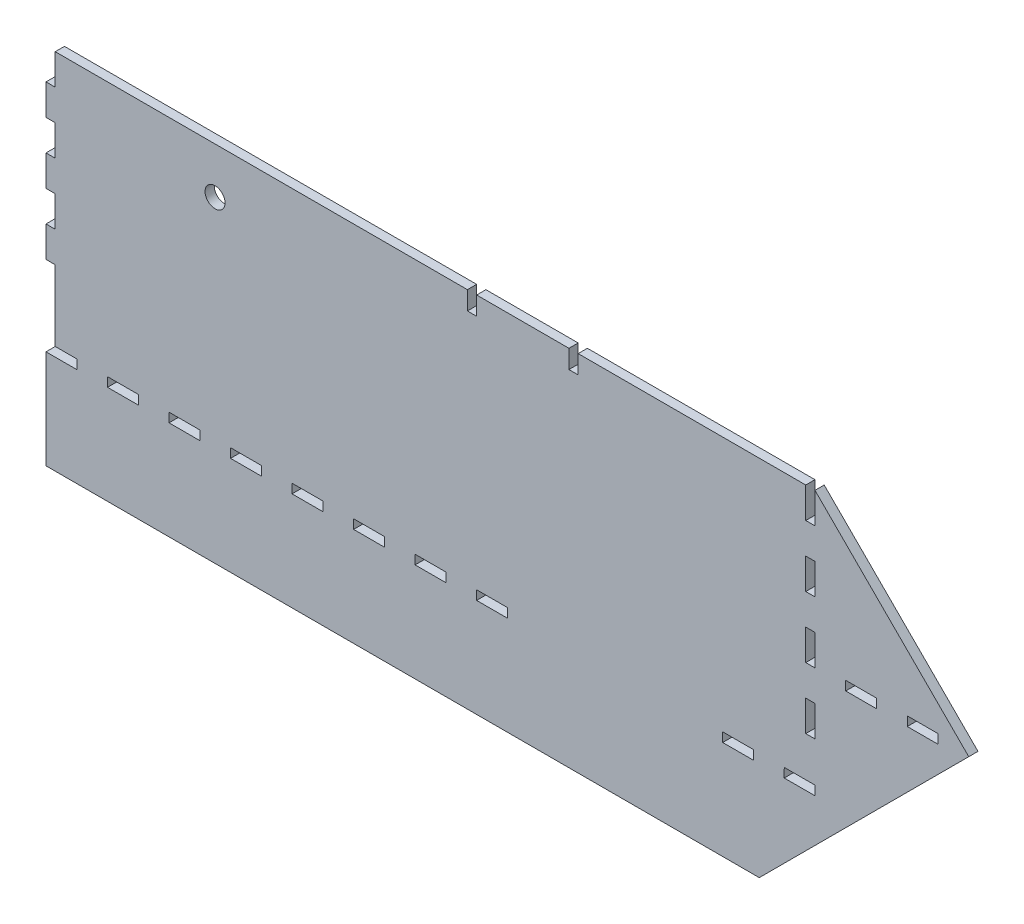
SolidWorks part; units mm, degrees
ref_plane "Front Plane" through (0, 0, 0) normal (0, 0, 1) x (1, 0, 0)
ref_plane "Top Plane" through (0, 0, 0) normal (0, 1, 0) x (1, 0, 0)
ref_plane "Right Plane" through (0, 0, 0) normal (1, 0, 0) x (0, 0, -1)
sketch "Sketch1" plane through (0, 0, 0) normal (0, 0, 1) x (1, 0, 0)
  line L0 (-112.631, -63.8403) -> (-112.631, -53.7284)
  line L1 (134.369, 32.2716) -> (60.379, 32.2716)
  line L2 (-72.631, -50.7284) -> (-62.631, -50.7284)
  line L3 (-62.631, 32.2716) -> (24.379, 32.2716)
  line L4 (137.369, 32.2716) -> (187.369, -17.7284)
  line L5 (187.369, -17.7284) -> (137.369, -67.7284)
  line L6 (-112.631, 17.2716) -> (-57.6695, 17.2716) construction
  line L7 (42.379, 32.2716) -> (27.379, 32.2716)
  line L8 (27.379, 32.2716) -> (27.379, 26.2716)
  line L9 (137.369, 32.2716) -> (137.369, -67.7284) construction
  line L10 (137.369, -17.7284) -> (187.369, -17.7284) construction
  line L11 (157.369, -16.2284) -> (147.369, -16.2284)
  line L12 (177.369, -16.2284) -> (167.369, -16.2284)
  line L13 (177.369, -16.2284) -> (177.369, -19.2284)
  line L14 (177.369, -19.2284) -> (167.369, -19.2284)
  line L15 (167.369, -16.2284) -> (167.369, -19.2284)
  line L16 (177.369, -16.2284) -> (167.369, -19.2284) construction
  line L17 (177.369, -19.2284) -> (167.369, -16.2284) construction
  line L18 (157.369, -16.2284) -> (157.369, -19.2284)
  line L19 (157.369, -19.2284) -> (147.369, -19.2284)
  line L20 (147.369, -16.2284) -> (147.369, -19.2284)
  line L21 (137.3812, -50.7284) -> (127.3812, -50.7284)
  line L22 (137.3812, -50.7284) -> (137.3692, -53.7284)
  line L23 (137.3692, -53.7284) -> (127.3692, -53.7284)
  line L24 (127.3812, -50.7284) -> (127.3692, -53.7284)
  line L25 (137.3812, -50.7284) -> (127.3692, -53.7284) construction
  line L26 (137.3692, -53.7284) -> (127.3812, -50.7284) construction
  line L27 (117.3811, -50.7284) -> (107.3787, -50.7284)
  line L28 (117.3811, -50.7284) -> (117.3691, -53.7284)
  line L29 (117.3691, -53.7284) -> (107.3691, -53.7284)
  line L30 (107.3787, -50.7284) -> (107.3691, -53.7284)
  line L31 (117.3811, -50.7284) -> (107.3691, -53.7284) construction
  line L32 (117.3691, -53.7284) -> (107.3787, -50.7284) construction
  line L33 (27.379, 26.2716) -> (24.379, 26.2716)
  line L34 (24.379, 26.2716) -> (24.379, 32.2716)
  line L35 (27.379, 32.2716) -> (57.379, 32.2716)
  line L36 (137.369, -67.7284) -> (119.2571, -85.8403)
  line L37 (60.379, 26.2716) -> (60.379, 32.2716)
  line L38 (57.379, 26.2716) -> (60.379, 26.2716)
  line L39 (57.379, 32.2716) -> (57.379, 26.2716)
  line L40 (57.379, 32.2716) -> (42.379, 32.2716)
  line L41 (60.379, 32.2716) -> (134.369, 32.2716)
  line L42 (119.2571, -85.8403) -> (-112.631, -85.8403)
  line L43 (-112.631, -85.8403) -> (-112.631, -63.8403)
  line L51 (37.3714, -50.7284) -> (27.369, -50.7284)
  line L52 (37.3714, -50.7284) -> (37.369, -53.7284)
  line L53 (37.369, -53.7284) -> (27.369, -53.7284)
  line L54 (27.369, -50.7284) -> (27.369, -53.7284)
  line L55 (37.3714, -50.7284) -> (27.369, -53.7284) construction
  line L56 (37.369, -53.7284) -> (27.369, -50.7284) construction
  line L57 (17.369, -50.7284) -> (7.369, -50.7284)
  line L58 (17.369, -50.7284) -> (17.369, -53.7284)
  line L59 (17.369, -53.7284) -> (7.369, -53.7284)
  line L60 (7.369, -50.7284) -> (7.369, -53.7284)
  line L61 (17.369, -50.7284) -> (7.369, -53.7284) construction
  line L62 (17.369, -53.7284) -> (7.369, -50.7284) construction
  line L63 (-2.631, -50.7284) -> (-12.631, -50.7284)
  line L64 (-2.631, -50.7284) -> (-2.631, -53.7284)
  line L65 (-2.631, -53.7284) -> (-12.631, -53.7284)
  line L66 (-12.631, -50.7284) -> (-12.631, -53.7284)
  line L67 (-2.631, -50.7284) -> (-12.631, -53.7284) construction
  line L68 (-2.631, -53.7284) -> (-12.631, -50.7284) construction
  line L69 (-22.631, -50.7284) -> (-32.631, -50.7284)
  line L70 (-22.631, -50.7284) -> (-22.631, -53.7284)
  line L71 (-22.631, -53.7284) -> (-32.631, -53.7284)
  line L72 (-32.631, -50.7284) -> (-32.631, -53.7284)
  line L73 (-22.631, -50.7284) -> (-32.631, -53.7284) construction
  line L74 (-22.631, -53.7284) -> (-32.631, -50.7284) construction
  line L75 (-42.631, -50.7284) -> (-52.631, -50.7284)
  line L76 (-42.631, -50.7284) -> (-42.631, -53.7284)
  line L77 (-42.631, -53.7284) -> (-52.631, -53.7284)
  line L78 (-52.631, -50.7284) -> (-52.631, -53.7284)
  line L79 (-42.631, -50.7284) -> (-52.631, -53.7284) construction
  line L80 (-42.631, -53.7284) -> (-52.631, -50.7284) construction
  line L82 (-62.631, -50.7284) -> (-62.631, -53.7284)
  line L83 (-62.631, -53.7284) -> (-72.631, -53.7284)
  line L84 (-72.631, -50.7284) -> (-72.631, -53.7284)
  line L85 (-62.631, -50.7284) -> (-72.631, -53.7284) construction
  line L86 (-62.631, -53.7284) -> (-72.631, -50.7284) construction
  line L87 (137.369, 12.2716) -> (134.369, 12.2716)
  line L88 (-82.631, -50.7284) -> (-82.631, -53.7284)
  line L89 (-82.631, -53.7284) -> (-92.631, -53.7284)
  line L90 (-92.631, -50.7284) -> (-92.631, -53.7284)
  line L91 (-82.631, -50.7284) -> (-92.631, -53.7284) construction
  line L92 (-82.631, -53.7284) -> (-92.631, -50.7284) construction
  line L94 (-102.631, -50.7284) -> (-102.631, -53.7284)
  line L95 (-102.631, -53.7284) -> (-112.631, -53.7284)
  line L97 (-102.631, -50.7284) -> (-112.631, -53.7284) construction
  line L98 (-102.631, -53.7284) -> (-107.631, -52.2284) construction
  line L99 (-62.631, -50.7284) -> (-72.631, -50.7284) [skipped]
  line L100 (-82.631, -50.7284) -> (-92.631, -50.7284) [skipped]
  line L101 (-102.631, -50.7284) -> (-112.631, -50.7284) [skipped]
  line L102 (137.369, 32.2716) -> (137.369, 22.2716)
  line L103 (137.369, 22.2716) -> (134.369, 22.2716)
  line L104 (134.369, 32.2716) -> (134.369, 22.2716)
  line L105 (137.369, 12.2716) -> (137.369, 2.2716)
  line L106 (137.369, 2.2716) -> (134.369, 2.2716)
  line L107 (134.369, 12.2716) -> (134.369, 2.2716)
  line L108 (137.369, -7.7284) -> (134.369, -7.7284)
  line L109 (137.369, -7.7284) -> (137.369, -17.7284)
  line L111 (137.369, -17.7284) -> (134.369, -17.7284)
  line L114 (157.369, -16.2284) -> (147.369, -19.2284) construction
  line L121 (134.369, -7.7284) -> (134.369, -17.7284)
  line L122 (157.369, -19.2284) -> (147.369, -16.2284) construction
  line L124 (-109.631, -50.7284) -> (-102.631, -50.7284)
  line L125 (-112.631, -52.2284) -> (-112.631, -53.3547) [skipped]
  line L126 (-62.631, 32.2716) -> (-109.631, 32.2716)
  line L127 (-112.631, -7.7284) -> (-109.631, -7.7284)
  line L128 (137.369, -27.7284) -> (134.369, -27.7284)
  line L129 (137.369, -27.7284) -> (137.369, -37.7284)
  line L130 (137.369, -37.7284) -> (134.369, -37.7284)
  line L131 (134.369, -27.7284) -> (134.369, -37.7284)
  line L132 (-112.631, 22.2716) -> (-112.631, 12.2716)
  line L133 (-109.631, -17.7284) -> (-112.631, -17.7284)
  line L134 (-112.631, -27.7284) -> (-109.631, -27.7284)
  line L135 (-109.631, -50.7284) -> (-109.631, -27.7284)
  line L136 (-109.631, 2.2716) -> (-112.631, 2.2716)
  line L137 (-112.631, 2.2716) -> (-112.631, -7.7284)
  line L138 (-109.631, 22.2716) -> (-109.631, 32.2716)
  line L139 (-109.631, 22.2716) -> (-112.631, 22.2716)
  line L140 (-112.631, 12.2716) -> (-109.631, 12.2716)
  line L141 (-109.631, -17.7284) -> (-109.631, -7.7284)
  line L142 (-112.631, -17.7284) -> (-112.631, -27.7284)
  line L143 (-109.631, 2.2716) -> (-109.631, 12.2716)
  line L144 (-92.631, -50.7284) -> (-82.631, -50.7284)
  circle A0 centre (-57.6695, 17.2716) radius 3.25
  point P5 (172.369, -17.7284)
  point P9 (151.1235, -51.5486)
  point P17 (152.369, -17.7284)
  point P19 (131.1235, -51.6165)
  point P24 (111.1235, -51.6845)
  point P44 (31.1235, -51.9564)
  point P49 (11.1235, -52.0244)
  point P54 (-8.8765, -52.0924)
  point P59 (-28.8765, -52.1604)
  point P64 (-48.8765, -52.2284)
  point P70 (-68.8765, -52.2284)
  point P75 (-88.8765, -52.2284)
  point P80 (-108.8765, -52.2284)
  dimension "D32" = 6.5
  dimension "D3" = 300
  dimension "D5" = 50
  dimension "D6" = 10
  dimension "D7" = 10
  dimension "D8" = 10
  dimension "D10" = 3
  dimension "D11" = 22
  dimension "D13" = 3
  dimension "D14" = 10
  dimension "D15" = 94.99
  dimension "D17" = 15
  dimension "D18" = 6
  dimension "D19" = 3
  dimension "D21" = 10
  dimension "D22" = 10
  dimension "D23" = 10
  dimension "D24" = 10
  dimension "D25" = 10
  dimension "D26" = 10
  dimension "D9" = 10
  dimension "D27" = 10
  dimension "D28" = 10
  dimension "D29" = 10
  dimension "D30" = 10
  dimension "D31" = 15
  dimension "D38" = 10
  dimension "D39" = 10
  dimension "D40" = 3
  dimension "D41" = 10
  dimension "D20" = 47
  dimension "D42" = 3
  dimension "D12" = 4
  dimension "D16" = 4
extrude "Boss-Extrude1" add sketch "Sketch1" along normal blind 3
